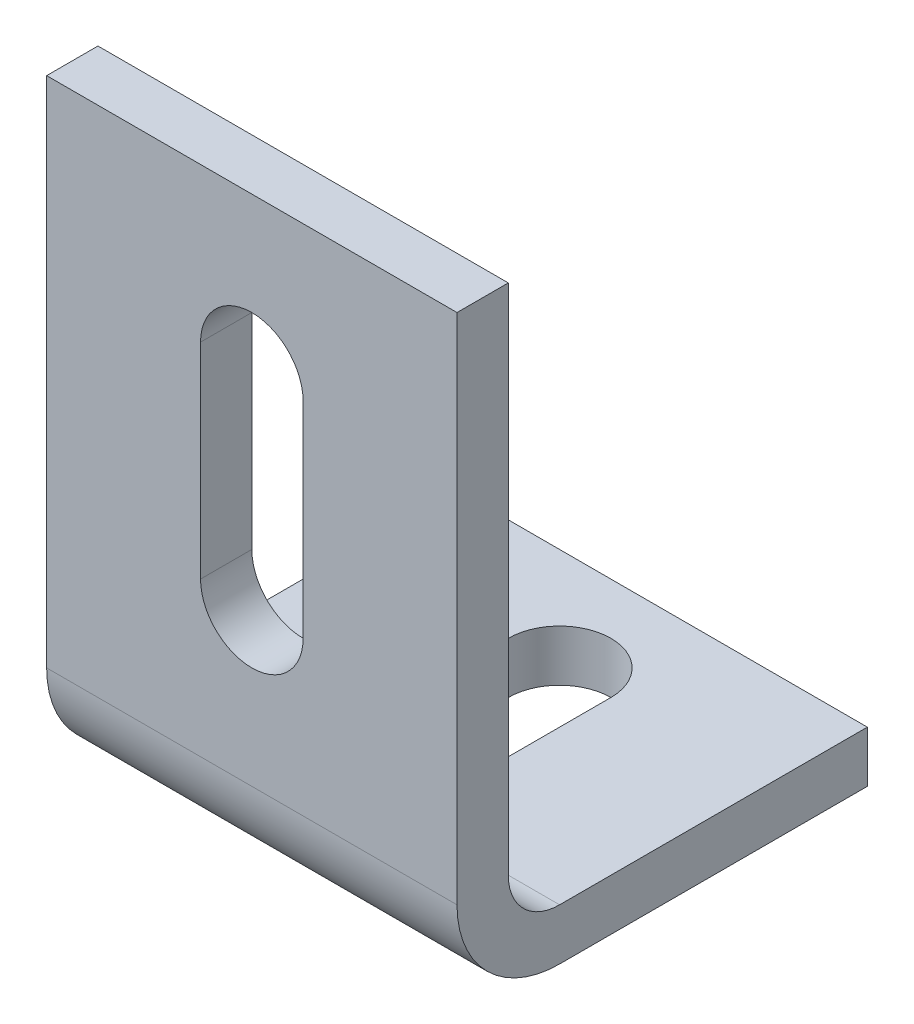
SolidWorks part; units mm, degrees
material "6061 Alloy"
ref_plane "Front Plane" through (0, 0, 0) normal (0, 0, 1) x (1, 0, 0)
ref_plane "Top Plane" through (0, 0, 0) normal (0, 1, 0) x (1, 0, 0)
ref_plane "Right Plane" through (0, 0, 0) normal (1, 0, 0) x (0, 0, -1)
sketch "Sketch1" plane through (0, 0, 0) normal (1, 0, 0) x (0, 0, -1)
  line L0 (0, 34.925) -> (0, 3.175) construction
  line L1 (3.175, 0) -> (22.225, 0) construction
  line L2 (-3.175, 34.925) -> (-3.175, 3.175) construction
  line L3 (3.175, -3.175) -> (22.225, -3.175) construction
  line L4 (22.225, 0) -> (22.225, -3.175) construction
  line L5 (-3.175, 34.925) -> (0, 34.925) construction
  line L8 (6.35, 0) -> (19.05, 0) construction
  line L9 (0, 28.575) -> (0, 9.525) construction
  arc A0 (0, 3.175) -> (3.175, 0) centre (3.175, 3.175) ccw construction
  arc A1 (-3.175, 3.175) -> (3.175, -3.175) centre (3.175, 3.175) ccw construction
  point P6 (0, 0)
  dimension "D2" = 6.35
  dimension "D3" = 12.7
  dimension "D1" = 6.35
  dimension "D4" = 9.525
sketch "Sketch2" plane through (0, 0, 0) normal (0, 0, 1) x (1, 0, 0)
  line L0 (-12.7, 0) -> (12.7, 0) construction
  line L2 (0, 25.4) -> (0, 12.7) construction
  line L4 (3.175, 25.4) -> (3.175, 12.7) construction
  line L5 (-3.175, 25.4) -> (-3.175, 12.7) construction
  line L7 (-3.175, 0) -> (3.175, 0) construction
  arc A0 (3.175, 25.4) -> (-3.175, 25.4) centre (0, 25.4) ccw construction
  arc A1 (-3.175, 12.7) -> (3.175, 12.7) centre (0, 12.7) ccw construction
  point P5 (0, 19.05)
  point P10 (0, 28.575)
  point P13 (0, 0)
  point P14 (0, 9.525)
  dimension "D1" = 6.35
  dimension "D2" = 6.35
sketch "Sketch3" plane through (0, 0, 0) normal (0, 1, 0) x (1, 0, 0)
  line L0 (0, 15.875) -> (0, 9.525) construction
  line L1 (3.175, 15.875) -> (3.175, 9.525) construction
  line L2 (-3.175, 15.875) -> (-3.175, 9.525) construction
  line L3 (0, 3.175) -> (0, 22.225) construction
  arc A0 (3.175, 15.875) -> (-3.175, 15.875) centre (0, 15.875) ccw construction
  arc A1 (-3.175, 9.525) -> (3.175, 9.525) centre (0, 9.525) ccw construction
  point P2 (0, 12.7)
  point P18 (0, 6.35)
  point P21 (0, 19.05)
  dimension "D1" = 6.35
sketch "Sketch4" plane through (0, 0, 0) normal (1, 0, 0) x (0, 0, -1)
  line L0 (0, 34.925) -> (0, 3.175) construction
  line L1 (3.175, 0) -> (22.225, 0) construction
  line L2 (3.175, -3.175) -> (22.225, -3.175) construction
  line L5 (-3.175, 34.925) -> (-3.175, 3.175) construction
  line L10 (3.175, -3.175) -> (22.225, -3.175)
  line L13 (-3.175, 34.925) -> (-3.175, 3.175)
  line L16 (0, 34.925) -> (0, 3.175) construction
  line L17 (3.175, 0) -> (22.225, 0) construction
  arc A0 (0, 3.175) -> (3.175, 0) centre (3.175, 3.175) ccw construction
  arc A4 (-3.175, 3.175) -> (3.175, -3.175) centre (3.175, 3.175) ccw construction
  arc A5 (-3.175, 3.175) -> (3.175, -3.175) centre (3.175, 3.175) ccw
  arc A6 (0, 3.175) -> (3.175, 0) centre (3.175, 3.175) ccw construction
  dimension "D1" = 25.4
  dimension "D2" = 38.1
  dimension "D3" = 90
extrude "Extrude-Thin1" add sketch "Sketch4" along normal mid plane 25.4 thin thin type one direction reverse wall 3.175
sketch "Sketch5" plane through (0, 0, 0) normal (0, 0, 1) x (1, 0, 0)
  line L0 (3.175, 25.4) -> (3.175, 12.7) construction
  line L1 (3.175, 25.4) -> (3.175, 12.7)
  line L2 (-3.175, 25.4) -> (-3.175, 12.7) construction
  line L3 (-3.175, 25.4) -> (-3.175, 12.7)
  arc A0 (-3.175, 12.7) -> (3.175, 12.7) centre (0, 12.7) ccw construction
  arc A1 (3.175, 25.4) -> (-3.175, 25.4) centre (0, 25.4) ccw construction
  arc A2 (-3.175, 12.7) -> (3.175, 12.7) centre (0, 12.7) ccw
  arc A3 (3.175, 25.4) -> (-3.175, 25.4) centre (0, 25.4) ccw
extrude "Cut-Extrude1" cut sketch "Sketch5" along normal through all
sketch "Sketch6" plane through (0, 0, 0) normal (0, 1, 0) x (1, 0, 0)
  line L0 (-3.175, 15.875) -> (-3.175, 9.525) construction
  line L1 (3.175, 15.875) -> (3.175, 9.525) construction
  line L2 (-3.175, 15.875) -> (-3.175, 9.525)
  line L3 (3.175, 15.875) -> (3.175, 9.525)
  arc A0 (-3.175, 9.525) -> (3.175, 9.525) centre (0, 9.525) ccw construction
  arc A1 (3.175, 15.875) -> (-3.175, 15.875) centre (0, 15.875) ccw construction
  arc A2 (-3.175, 9.525) -> (3.175, 9.525) centre (0, 9.525) ccw
  arc A3 (3.175, 15.875) -> (-3.175, 15.875) centre (0, 15.875) ccw
extrude "Cut-Extrude2" cut sketch "Sketch6" against normal through all
equation "\"D2@Sketch2\"=\"D1@Sketch2\""
equation "\"D1@Sketch3\" = \"D1@Sketch2\""
equation "\"D5@Extrude-Thin1\"=\"THICKNESS@Sketch1\""
equation "\"D1@Extrude-Thin1\"=\"Length@Sketch2\""
